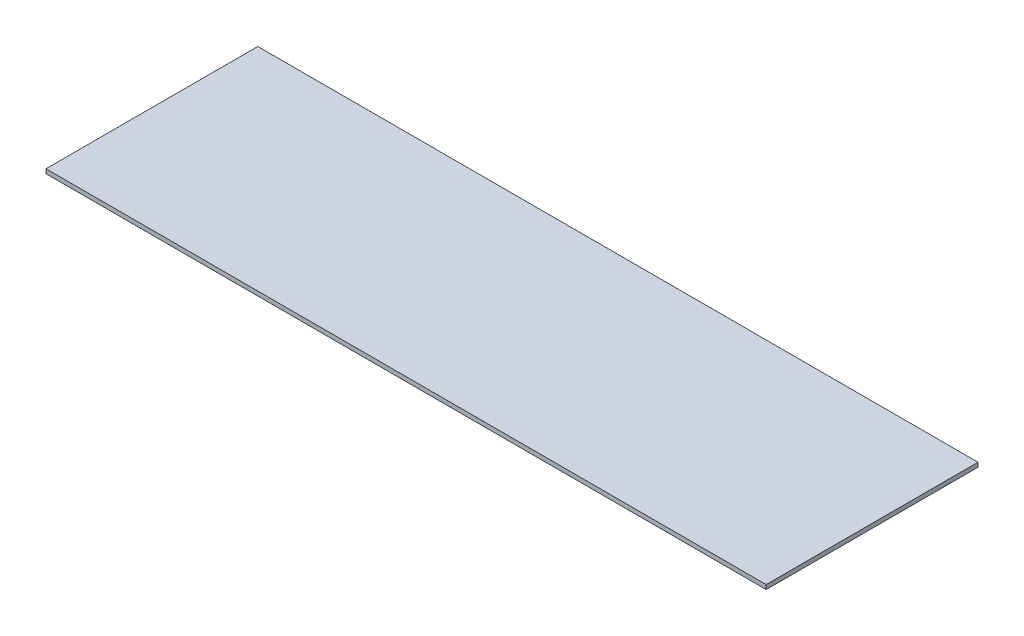
SolidWorks part; units mm, degrees
ref_plane "Front Plane" through (0, 0, 0) normal (0, 0, 1) x (1, 0, 0)
ref_plane "Top Plane" through (0, 0, 0) normal (0, 1, 0) x (1, 0, 0)
ref_plane "Right Plane" through (0, 0, 0) normal (1, 0, 0) x (0, 0, -1)
sketch "Sketch1" plane through (0, 0, 0) normal (0, 1, 0) x (1, 0, 0)
  line L1 (0, 0) -> (215.9, 0)
  line L2 (0, 0) -> (0, 63.5)
  line L3 (0, 63.5) -> (215.9, 63.5)
  line L4 (215.9, 0) -> (215.9, 63.5)
  dimension "D1" = 215.9
  dimension "D2" = 63.5
extrude "Boss-Extrude1" add sketch "Sketch1" along normal blind 1.2954
